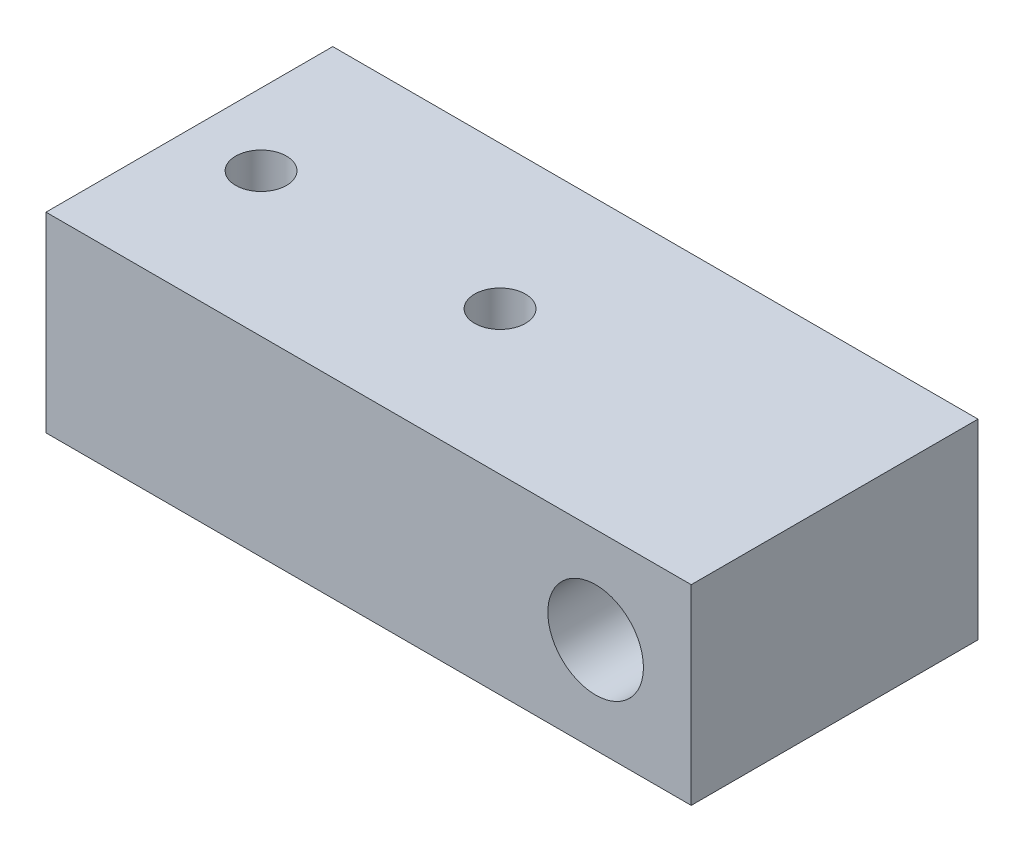
SolidWorks part; units mm, degrees
material "Plain Carbon Steel"
ref_plane "Front Plane" through (0, 0, 0) normal (0, 0, 1) x (1, 0, 0)
ref_plane "Top Plane" through (0, 0, 0) normal (0, 1, 0) x (1, 0, 0)
ref_plane "Right Plane" through (0, 0, 0) normal (1, 0, 0) x (0, 0, -1)
sketch "Sketch1" plane through (0, 0, 0) normal (0, 1, 0) x (1, 0, 0)
  line L1 (-42.8625, 19.05) -> (42.8625, 19.05)
  line L2 (-42.8625, 19.05) -> (-42.8625, -19.05)
  line L3 (-42.8625, -19.05) -> (42.8625, -19.05)
  line L4 (42.8625, 19.05) -> (42.8625, -19.05)
  line L5 (-42.8625, 19.05) -> (42.8625, -19.05) construction
  line L6 (-42.8625, -19.05) -> (42.8625, 19.05) construction
  point P0 (0, 0)
  dimension "D1" = 85.725
  dimension "D2" = 38.1
extrude "Boss-Extrude1" add sketch "Sketch1" along normal mid plane 25.4
hole_wizard "1/2 (0.5) Diameter Hole1" positions "Sketch2" profile "Sketch3" hole size "1/2" standard "ANSI Inch" end condition through all
sketch "Sketch2" plane through (0, 0, 19.05) normal (0, 0, 1) x (1, 0, 0)
  line L0 (-42.8625, -12.7) -> (42.8625, -12.7) construction
  line L1 (42.8625, 12.7) -> (42.8625, -12.7) construction
  line L2 (-42.8625, 12.7) -> (-42.8625, -12.7) construction
  point P0 (30.1625, 0)
  dimension "D1" = 12.7
  dimension "D2" = 12.7
  dimension "D3" = 73.025
sketch "Sketch3" plane through (30.1625, 0, 19.05) normal (1, 0, 0) x (0, -1, 0)
  line L0 (0, 0) -> (0, 38.1)
  line L1 (0, 38.1) -> (6.35, 38.1)
  line L2 (6.35, 38.1) -> (6.35, 0)
  line L5 (6.35, 0) -> (0, 0)
  line L11 (0, -6.35) -> (0, 107.95) construction
  dimension "Thru Hole Dia." = 12.7
  dimension "Thru Hole Depth" = 38.1
hole_wizard "1/4 Clearance Hole1" positions "Sketch4" profile "Sketch5" hole size "1/4" standard "ANSI Inch" end condition through all
sketch "Sketch4" plane through (0, 12.7, 0) normal (0, 1, 0) x (1, 0, 0)
  line L0 (42.8625, 19.05) -> (-42.8625, 19.05) construction
  line L3 (42.8625, -19.05) -> (42.8625, 19.05) construction
  point P0 (-33.3375, 0)
  point P2 (-1.5875, 0)
  dimension "D1" = 19.05
  dimension "D2" = 31.75
  dimension "D3" = 44.45
sketch "Sketch5" plane through (-33.3375, 12.7, 0) normal (1, 0, 0) x (0, 0, 1)
  line L0 (0, 0) -> (0, 25.4)
  line L1 (0, 25.4) -> (3.3782, 25.4)
  line L2 (3.3782, 25.4) -> (3.3782, 0)
  line L5 (3.3782, 0) -> (0, 0)
  line L11 (0, -6.35) -> (0, 107.95) construction
  dimension "Thru Hole Dia." = 6.7564
  dimension "Thru Hole Depth" = 25.4
sketch "Sketch6" plane through (0, 0, -19.05) normal (0, 0, -1) x (-1, 0, 0)
  line L0 (-159.1006, -55.2481) -> (-14.1596, -8.1539) construction
  line L1 (-159.1006, -55.2481) -> (-166.9496, -31.0913) construction
  line L2 (-14.1596, -8.1539) -> (-22.0086, 16.0029) construction
  line L3 (-166.9496, -31.0913) -> (-22.0086, 16.0029) construction
  line L4 (-42.8625, -12.7) -> (42.8625, -12.7) construction
  line L5 (-42.8625, 12.7) -> (-42.8625, 8.7191)
  line L6 (-42.8625, 12.7) -> (-42.8625, -12.7) construction
  line L7 (-42.8625, 8.7191) -> (-29.6545, 12.7)
  line L8 (-42.8625, 12.7) -> (42.8625, 12.7) construction
  line L9 (-29.6545, 12.7) -> (-42.8625, 12.7)
  circle A0 centre (-30.1625, 0) radius 6.35 construction
  point P0 (-30.1625, 0)
  point P21 (-42.8625, 9.2271)
  dimension "D1" = 152.4
  dimension "D2" = 25.4
  dimension "D3" = 12.7
  dimension "D4" = 12.7
  dimension "D5" = 18
  dimension "D6" = 0.508
  dimension "D7" = 0.508
